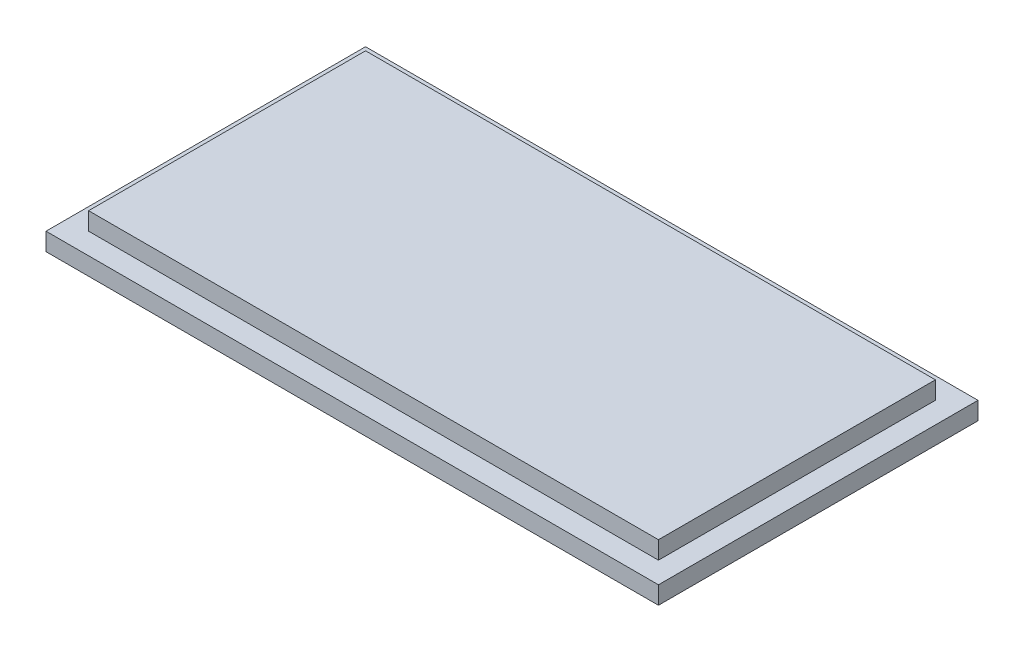
SolidWorks part; units mm, degrees
ref_plane "Front" through (0, 0, 0) normal (0, 0, 1) x (1, 0, 0)
ref_plane "Top" through (0, 0, 0) normal (0, 1, 0) x (1, 0, 0)
ref_plane "Right" through (0, 0, 0) normal (1, 0, 0) x (0, 0, -1)
sketch "Sketch1" plane through (0, 0, 0) normal (0, 1, 0) x (1, 0, 0)
  line L5 (-17.25, 9) -> (17.25, 9)
  line L6 (-17.25, 9) -> (-17.25, -9)
  line L7 (-17.25, -9) -> (17.25, -9)
  line L8 (17.25, 9) -> (17.25, -9)
  line L9 (-17.25, 9) -> (17.25, -9) construction
  line L10 (-17.25, -9) -> (17.25, 9) construction
  point P0 (0, 0)
  dimension "D1" = 34.5
  dimension "D2" = 18
extrude "Boss-Extrude1" add sketch "Sketch1" along normal blind 1
sketch "Sketch2" plane through (0, 1, 0) normal (0, 1, 0) x (1, 0, 0)
  line L1 (-16.05, 7.8) -> (16.05, 7.8)
  line L2 (-16.05, 7.8) -> (-16.05, -7.8)
  line L3 (-16.05, -7.8) -> (16.05, -7.8)
  line L4 (16.05, 7.8) -> (16.05, -7.8)
  line L5 (-16.05, 7.8) -> (16.05, -7.8) construction
  line L6 (-16.05, -7.8) -> (16.05, 7.8) construction
  point P0 (0, 0)
  dimension "D1" = 15.6
  dimension "D2" = 32.1
extrude "Boss-Extrude2" add sketch "Sketch2" along normal blind 1
